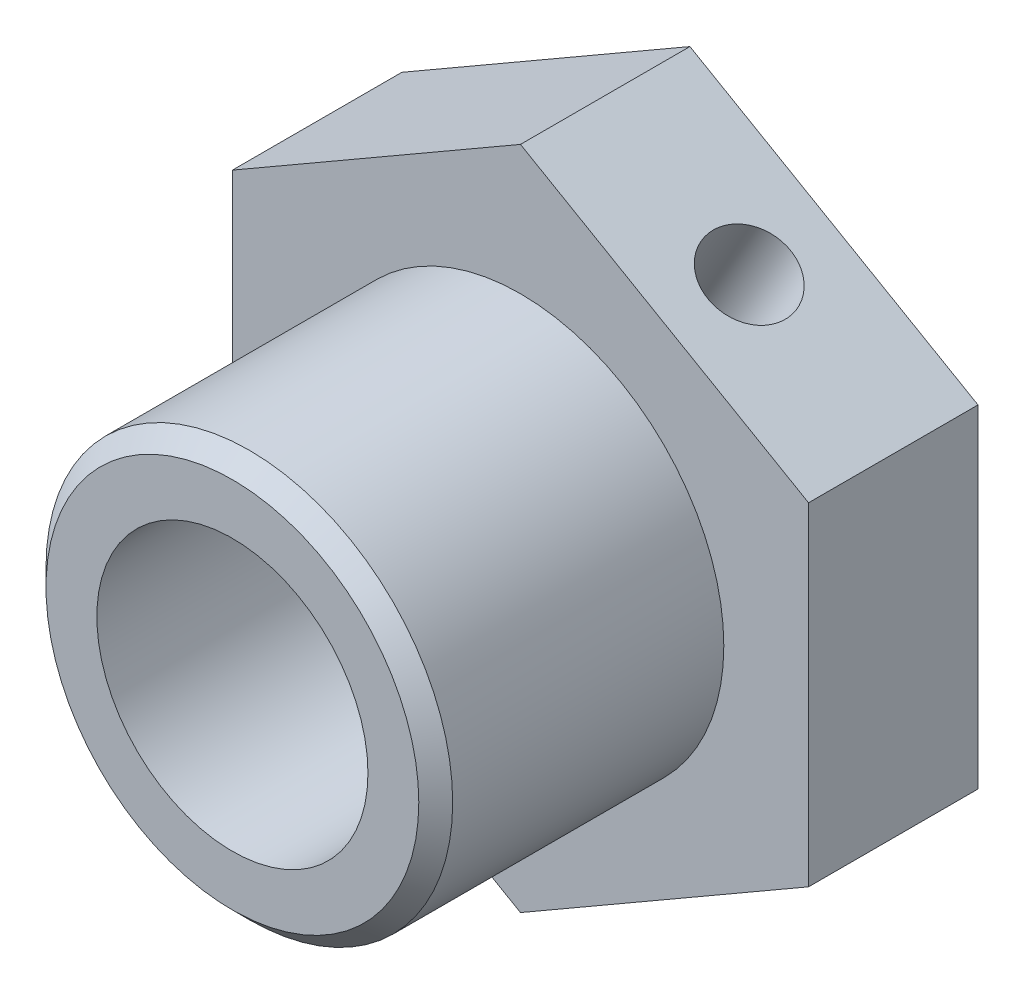
SolidWorks part; units mm, degrees
ref_plane "Alzado" through (0, 0, 0) normal (0, 0, 1) x (1, 0, 0)
ref_plane "Planta" through (0, 0, 0) normal (0, 1, 0) x (1, 0, 0)
ref_plane "Vista lateral" through (0, 0, 0) normal (1, 0, 0) x (0, 0, -1)
sketch "Croquis1" plane through (0, 0, 0) normal (0, 0, 1) x (1, 0, 0)
  line L1 (0, 9.815) -> (-8.5, 4.9075)
  line L2 (-8.5, 4.9075) -> (-8.5, -4.9075)
  line L3 (-8.5, -4.9075) -> (0, -9.815)
  line L4 (0, -9.815) -> (8.5, -4.9075)
  line L5 (8.5, -4.9075) -> (8.5, 4.9075)
  line L6 (8.5, 4.9075) -> (0, 9.815)
  circle A0 centre (0, 0) radius 8.5 construction
  dimension "D1" = 17
extrude "Saliente-Extruir1" add sketch "Croquis1" along normal blind 5
sketch "Croquis2" plane through (0, 0, 5) normal (0, 0, 1) x (1, 0, 0)
  circle A0 centre (0, 0) radius 6
  dimension "D1" = 12
extrude "Saliente-Extruir2" add sketch "Croquis2" along normal blind 8.5
sketch "Croquis3" plane through (0, 0, 13.5) normal (0, 0, 1) x (1, 0, 0)
  circle A0 centre (0, 0) radius 4
  dimension "D1" = 8
extrude "Cortar-Extruir1" cut sketch "Croquis3" against normal through all
chamfer "Chaflán1" distance 0.5 angle 45 1 edges at (6, 0, 13.5)
sketch "Croquis4" plane through (4.25, 7.3612, 0) normal (0.5, 0.866, 0) x (0.866, -0.5, 0)
  line L0 (4.9075, 0) -> (-4.9075, 0) construction
  circle A0 centre (0, -2.5) radius 1.225
  dimension "D1" = 2.45
  dimension "D2" = 2.5
extrude "Cortar-Extruir2" cut sketch "Croquis4" against normal through all
